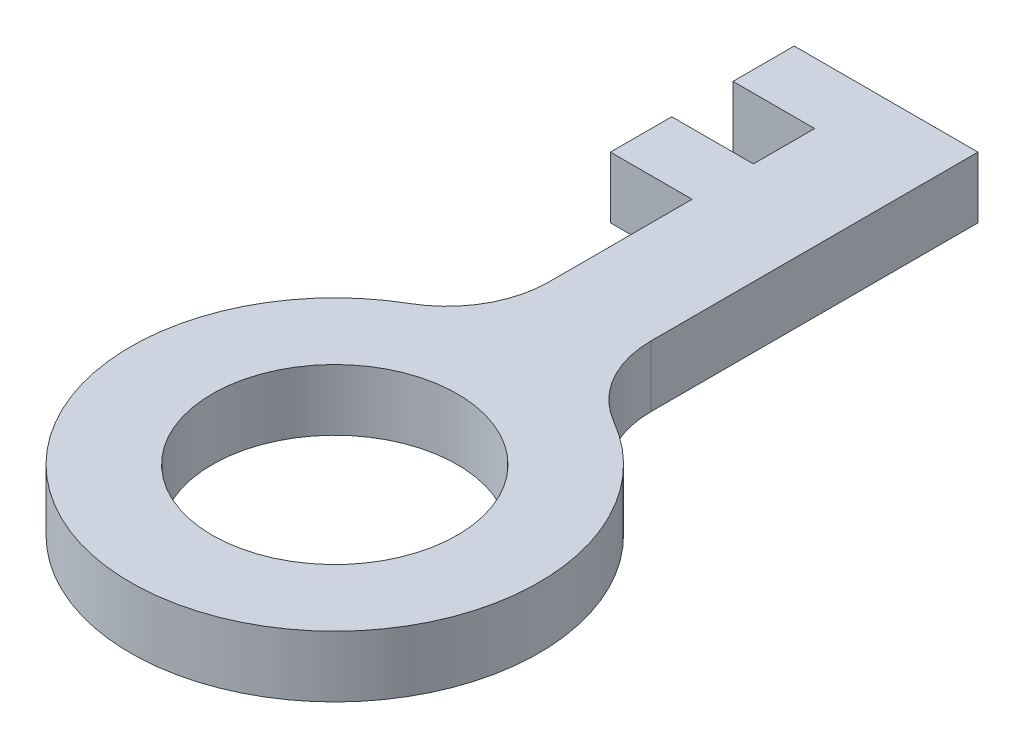
SolidWorks part; units mm, degrees
ref_plane "Front Plane" through (0, 0, 0) normal (0, 0, 1) x (1, 0, 0)
ref_plane "Top Plane" through (0, 0, 0) normal (0, 1, 0) x (1, 0, 0)
ref_plane "Right Plane" through (0, 0, 0) normal (1, 0, 0) x (0, 0, -1)
sketch "Sketch1" plane through (0, 0, 0) normal (0, 1, 0) x (1, 0, 0)
  circle A0 centre (0, 0) radius 10
  dimension "D1" = 20
extrude "Boss-Extrude1" add sketch "Sketch1" along normal blind 3
sketch "Sketch2" plane through (0, 3, 0) normal (0, 1, 0) x (1, 0, 0)
  line L5 (-2.5, 9) -> (2.5, 9)
  line L6 (-2.5, 9) -> (-2.5, 29)
  line L7 (-2.5, 29) -> (2.5, 29)
  line L8 (2.5, 9) -> (2.5, 29)
  circle A2 centre (0, 0) radius 10 construction
  point P4 (0, 0)
  point P10 (0, 0)
  point P11 (0.1864, 9)
  dimension "D1" = 20
  dimension "D2" = 5
  dimension "D3" = 2.5
  dimension "D4" = 9
extrude "Boss-Extrude2" add sketch "Sketch2" against normal blind 3
sketch "Sketch3" plane through (-2.5, 0, 0) normal (-1, 0, 0) x (0, 0, 1)
  line L0 (-29, 3) -> (-9.6825, 3) construction
  line L1 (-29, 0) -> (-26, 0)
  line L2 (-29, 0) -> (-29, 3)
  line L3 (-29, 3) -> (-26, 3)
  line L4 (-26, 0) -> (-26, 3)
  line L5 (-29, 0) -> (-9.6825, 0) construction
  line L6 (-23, 0) -> (-20, 0)
  line L7 (-23, 0) -> (-23, 3)
  line L8 (-23, 3) -> (-20, 3)
  line L9 (-20, 0) -> (-20, 3)
  dimension "D1" = 3
  dimension "D2" = 3
  dimension "D3" = 3
extrude "Boss-Extrude3" add sketch "Sketch3" along normal blind 4
sketch "Sketch4" plane through (0, 3, 0) normal (0, 1, 0) x (1, 0, 0)
  circle A0 centre (0, 0) radius 6
  dimension "D1" = 12
extrude "Cut-Extrude1" cut sketch "Sketch4" against normal blind 3
fillet "Fillet1" radius 5 2 edges at (-2.5, 1.5, -9.6825) (2.5, 1.5, -9.6825)
